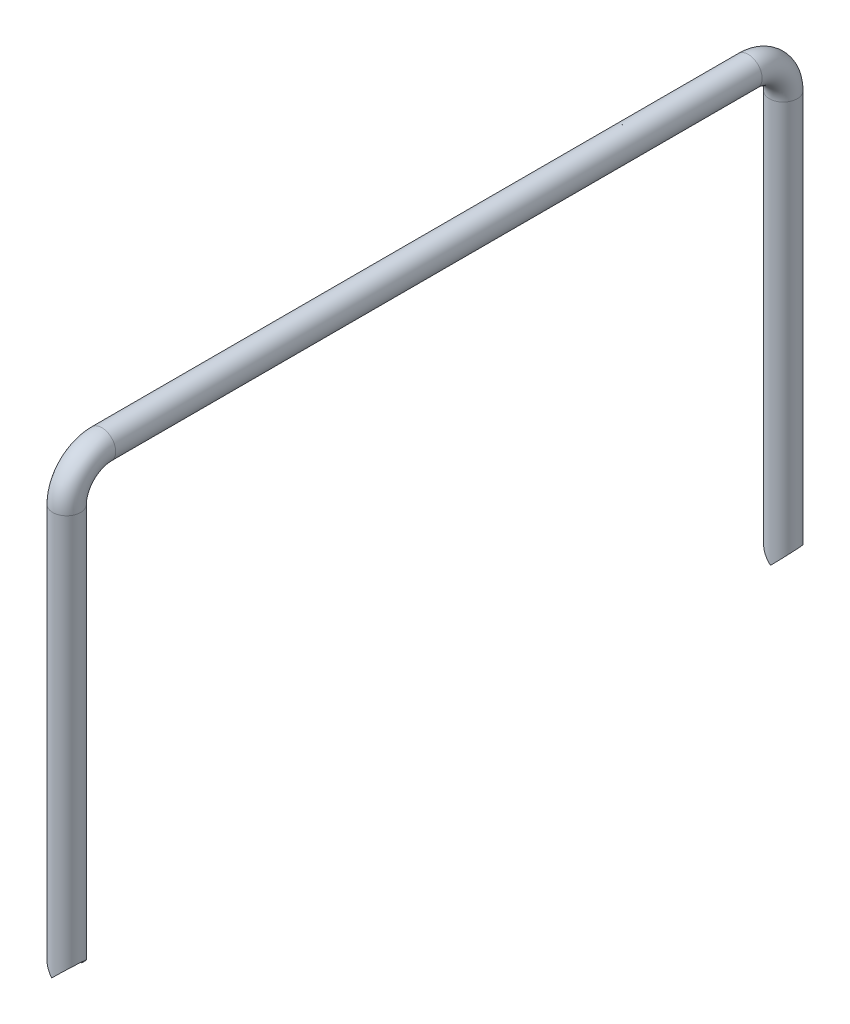
SolidWorks part; units mm, degrees
material "AISI 304"
ref_plane "Plano frontal" through (0, 0, 0) normal (0, 0, 1) x (1, 0, 0)
ref_plane "Plano superior" through (0, 0, 0) normal (0, 1, 0) x (1, 0, 0)
ref_plane "Plano direito" through (0, 0, 0) normal (1, 0, 0) x (0, 0, -1)
ref_plane "Plano1" through (0, 250, 0) normal (0, 1, 0) x (1, 0, 0)
sketch "Esboço1" plane through (0, 0, 0) normal (0, 1, 0) x (1, 0, 0)
  line L0 (0, 162.7552) -> (0, -162.7552)
  line L1 (0, 0) -> (910, 0) construction
  line L2 (910, 265) -> (910, -265) construction
  line L3 (37.1501, 202.6536) -> (910, 265)
  line L4 (37.1501, -202.6536) -> (910, -265)
  arc A0 (0, -162.7552) -> (37.1501, -202.6536) centre (40, -162.7552) ccw
  arc A1 (0, 162.7552) -> (37.1501, 202.6536) centre (40, 162.7552) cw
  point P9 (0, -200)
  point P12 (0, 200)
  dimension "D3" = 40
  dimension "D1" = 400
  dimension "D2" = 910
  dimension "D4" = 530
sketch "Esboço2" plane through (0, 250, 0) normal (0, 1, 0) x (1, 0, 0)
  line L0 (0, 162.7552) -> (0, -162.7552) construction
  line L1 (0, 0) -> (910, 0) construction
  line L2 (910, 265) -> (910, -265) construction
  line L3 (37.1501, 202.6536) -> (910, 265) construction
  line L4 (37.1501, -202.6536) -> (910, -265) construction
  arc A0 (0, -162.7552) -> (37.1501, -202.6536) centre (40, -162.7552) ccw construction
  arc A1 (0, 162.7552) -> (37.1501, 202.6536) centre (40, 162.7552) cw construction
  point P9 (0, -200)
  point P12 (0, 200)
  dimension "D3" = 40
  dimension "D1" = 400
  dimension "D2" = 910
  dimension "D4" = 530
sketch3d "3DSketch1"
  line L0 (37.1501, 0, 202.6536) -> (910, 0, 265) construction
  line L1 (58.5316, 250, 185.1239) -> (58.5316, 250, 204.1808) construction
  line L2 (58.5316, 250, -185.0557) -> (58.5316, 250, -204.1808) construction
  line L4 (58.5316, 250, -184.1808) -> (58.5316, 250, 184.1808)
  line L7 (58.5316, 250, 185.1239) -> (58.5316, 250, -185.0557) construction
  line L8 (58.5316, 230, 204.1808) -> (58.5316, 0, 204.1808)
  line L11 (58.5316, 230, -204.1808) -> (58.5316, 0, -204.1808)
  line L12 (0, 250, -162.7552) -> (0, 250, 162.7552) construction
  line L14 (37.1501, 0, -202.6536) -> (910, 0, -265) construction
  arc A0 (58.5316, 230, -204.1808) -> (58.5316, 250, -184.1808) centre (58.5316, 230, -184.1808) ccw
  arc A1 (58.5316, 230, 204.1808) -> (58.5316, 250, 184.1808) centre (58.5316, 230, 184.1808) ccw
  point P5 (58.5316, 250, -204.1808)
  point P7 (78.5316, 230, -184.1808)
  point P11 (58.5316, 250, 204.1808)
  point P13 (38.5316, 230, 184.1808)
  point P17 (37.1501, 0, -202.6536)
  point P18 (87.0231, 0, -206.2159)
  point P34 (196.7435, 15.88, -214.0531)
  dimension "D2" = 20
  dimension "D13" = 58.5316
sketch "Esboço4" plane through (0, 250, 0) normal (0, 1, 0) x (1, 0, 0)
  line L0 (60.0173, 204.287) -> (60.0173, -204.287) construction
  line L1 (37.1501, 202.6536) -> (910, 265) construction
  line L2 (0, 200) -> (0, -200) construction
  line L3 (0, -200) -> (910, -265) construction
  line L4 (0, 0) -> (910, 0) construction
  line L5 (910, -265) -> (910, 265) construction
  line L6 (910, 265) -> (0, 200) construction
  point P3 (60.0173, 0)
other "Pipe - configured 21.3 X 2.3(1)"
ref_plane "Plano2" through (58.5316, 230, 204.1808) normal (0, -1, 0) x (1, 0, 0)
sketch "Sketch1" plane through (58.5316, 230, 204.1808) normal (0, -1, 0) x (1, 0, 0)
  circle A0 centre (0, 0) radius 6.4375
  circle A1 centre (0, 0) radius 7.9375
  point P3 (0, 0)
  dimension "Out_dia" = 15.875
  dimension "D1" = 1.5
sketch "Esboço6" plane through (0, 0, 0) normal (0, 0, 1) x (1, 0, 0)
  circle A0 centre (0, 0) radius 7.9375
sweep "Varredura de corte1" cut profiles "Esboço6" path "Esboço1"
ref_plane "Plano3" through (0, 257.9375, 0) normal (0, 1, 0) x (1, 0, 0)
sketch "Esboço7" plane through (0, 257.9375, 0) normal (0, 1, 0) x (1, 0, 0)
  line L0 (0, 162.7552) -> (0, -162.7552) construction
  line L1 (0, 0) -> (910, 0) construction
  line L2 (910, 265) -> (910, -265) construction
  line L3 (37.1501, 202.6536) -> (910, 265) construction
  line L4 (37.1501, -202.6536) -> (910, -265) construction
  arc A0 (0, -162.7552) -> (37.1501, -202.6536) centre (40, -162.7552) ccw construction
  arc A1 (0, 162.7552) -> (37.1501, 202.6536) centre (40, 162.7552) cw construction
  point P9 (0, -200)
  point P12 (0, 200)
  dimension "D3" = 40
  dimension "D1" = 400
  dimension "D2" = 910
  dimension "D4" = 530
